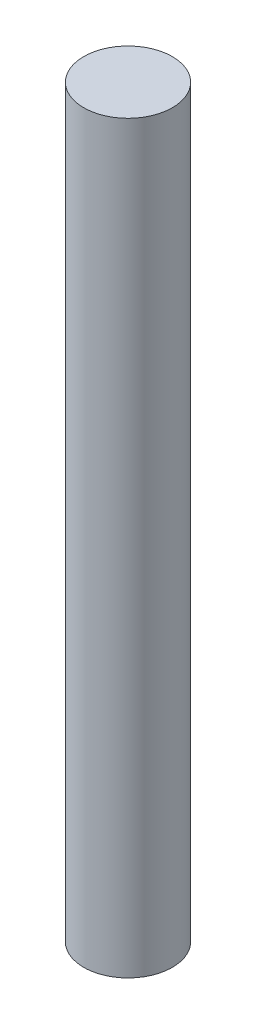
SolidWorks part; units mm, degrees
ref_plane "前视基准面" through (0, 0, 0) normal (0, 0, 1) x (1, 0, 0)
ref_plane "上视基准面" through (0, 0, 0) normal (0, 1, 0) x (1, 0, 0)
ref_plane "右视基准面" through (0, 0, 0) normal (1, 0, 0) x (0, 0, -1)
other "Configuration Table"
sketch "草图1" plane through (0, 0, 0) normal (0, 1, 0) x (1, 0, 0)
  circle A0 centre (0, 0) radius 2.5
extrude "凸台-拉伸1" add sketch "草图1" along normal blind 42
